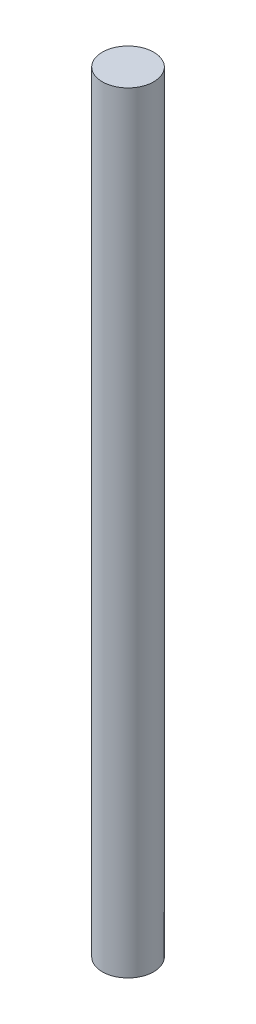
SolidWorks part; units mm, degrees
ref_plane "Plan de face" through (0, 0, 0) normal (0, 0, 1) x (1, 0, 0)
ref_plane "Plan de dessus" through (0, 0, 0) normal (0, 1, 0) x (1, 0, 0)
ref_plane "Plan de droite" through (0, 0, 0) normal (1, 0, 0) x (0, 0, -1)
sketch "Sketch1" plane through (0, 0, 0) normal (0, 1, 0) x (1, 0, 0)
  circle A0 centre (0, 0) radius 1.5
  dimension "D1" = 3
extrude "Boss-Extrude1" add sketch "Sketch1" along normal blind 45
